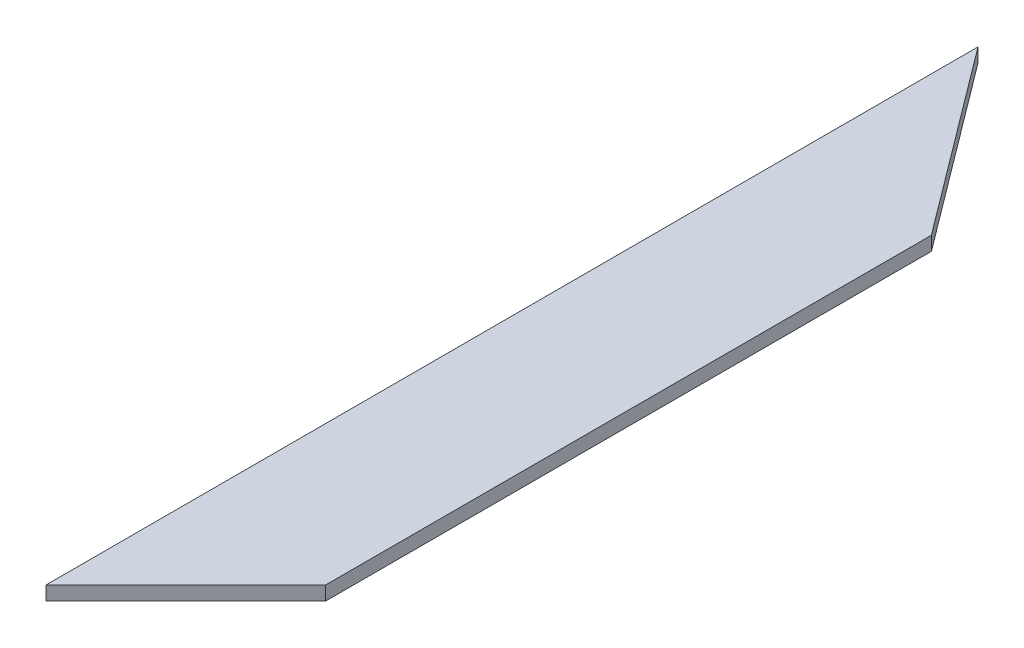
SolidWorks part; units mm, degrees
ref_plane "Спереди" through (0, 0, 0) normal (0, 0, 1) x (1, 0, 0)
ref_plane "Сверху" through (0, 0, 0) normal (0, 1, 0) x (1, 0, 0)
ref_plane "Справа" through (0, 0, 0) normal (1, 0, 0) x (0, 0, -1)
sketch "Эскиз1" plane through (0, 0, 0) normal (0, 1, 0) x (1, 0, 0)
  line L0 (0, 0) -> (0, 200)
  line L1 (0, 200) -> (30, 160)
  line L2 (30, 160) -> (30, 30)
  line L3 (30, 30) -> (0, 0)
  point P7 (-123.6561, 186.072)
  dimension "D1" = 200
  dimension "D2" = 30
  dimension "D3" = 40
  dimension "D4" = 30
extrude "Бобышка-Вытянуть1" add sketch "Эскиз1" along normal blind 3
